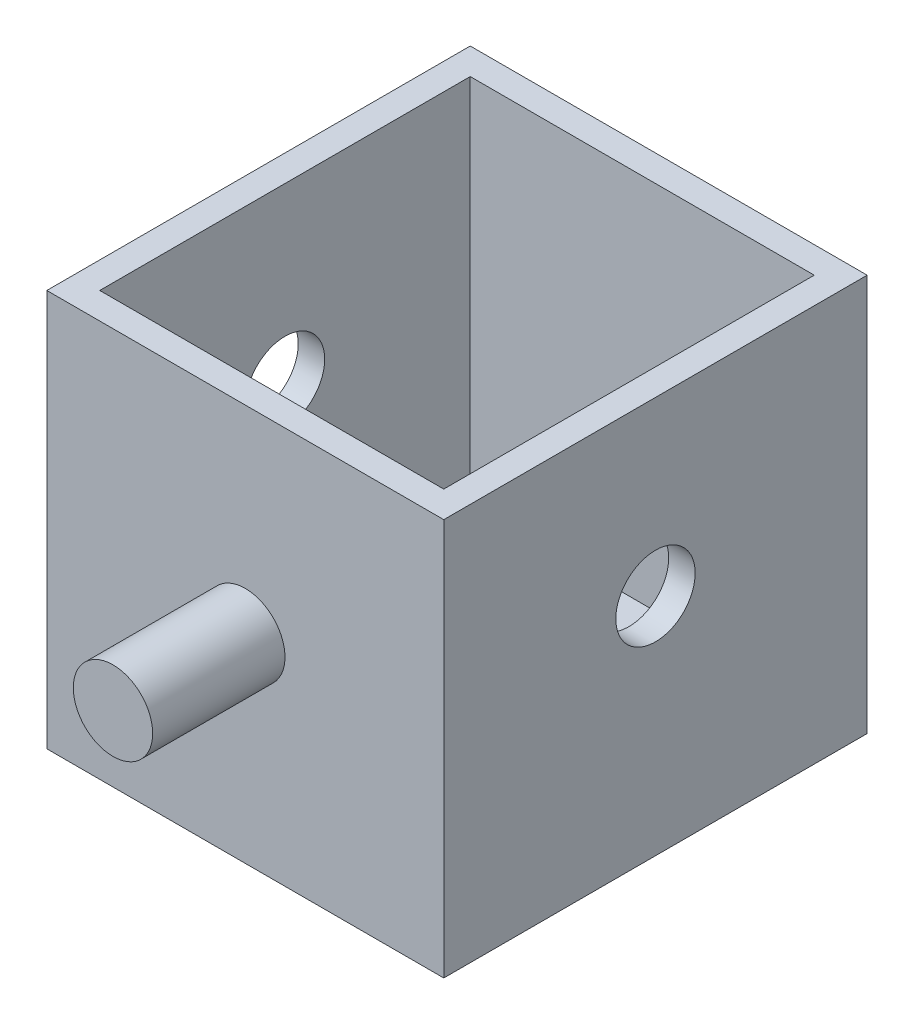
SolidWorks part; units mm, degrees
ref_plane "Front Plane" through (0, 0, 0) normal (0, 0, 1) x (1, 0, 0)
ref_plane "Top Plane" through (0, 0, 0) normal (0, 1, 0) x (1, 0, 0)
ref_plane "Right Plane" through (0, 0, 0) normal (1, 0, 0) x (0, 0, -1)
sketch "Sketch1" plane through (0, 0, 0) normal (0, 0, 1) x (1, 0, 0)
  line L1 (-19.05, -19.05) -> (19.05, -19.05)
  line L2 (-19.05, -19.05) -> (-19.05, 19.05)
  line L3 (-19.05, 19.05) -> (19.05, 19.05)
  line L4 (19.05, -19.05) -> (19.05, 19.05)
  line L5 (-19.05, -19.05) -> (19.05, 19.05) construction
  line L6 (-19.05, 19.05) -> (19.05, -19.05) construction
  point P0 (0, 0)
  dimension "D1" = 38.1
  dimension "D2" = 38.1
extrude "main body" add sketch "Sketch1" along normal blind 40.64
shell "hollow it" thickness 2.54
ref_point "cut point"
sketch "Sketch2" plane through (19.05, 0, 0) normal (1, 0, 0) x (0, 0, -1)
  line L0 (-40.64, -19.05) -> (0, -19.05) construction
  circle A0 centre (-20.32, 2.54) radius 3.81
  point P2 (0, 0)
  point P3 (-20.32, -19.05)
  dimension "D1" = 21.59
  dimension "D2" = 20.32
ref_point "bigger nibble point"
ref_point "bigger nibble here, too"
sketch "Sketch3" plane through (0, 0, 40.64) normal (0, 0, 1) x (1, 0, 0)
  circle A0 centre (0, 0) radius 3.81
  dimension "D1" = 7.62
extrude "nibble no 1" add sketch "Sketch3" along normal blind 12.7
sketch "Sketch4" plane through (0, 0, 0) normal (0, 0, -1) x (-1, 0, 0)
  circle A0 centre (0, 0) radius 3.81
  dimension "D1" = 7.62
extrude "nibble no 2" add sketch "Sketch4" along normal blind 12.7
ref_point "nibble center"
ref_plane "nibble flag plane" through (0, 0, 0) normal (0, -1, 0) x (-1, 0, 0)
sketch "Sketch5" plane through (0, 0, 0) normal (0, -1, 0) x (-1, 0, 0)
  line L1 (-0.8217, 4.4483) -> (0.4483, 4.4483)
  line L2 (-0.8217, 4.4483) -> (-0.8217, 8.2583)
  line L3 (-0.8217, 8.2583) -> (0.4483, 8.2583)
  line L4 (0.4483, 4.4483) -> (0.4483, 8.2583)
  line L5 (-0.8217, 4.4483) -> (0.4483, 8.2583) construction
  line L6 (-0.8217, 8.2583) -> (0.4483, 4.4483) construction
  point P0 (-0.1867, 6.3533)
  dimension "D1" = 1.27
  dimension "D2" = 3.81
extrude "flag" add sketch "Sketch5" along normal blind 0.254
extrude "nibble holes" cut sketch "Sketch2" against normal through all
